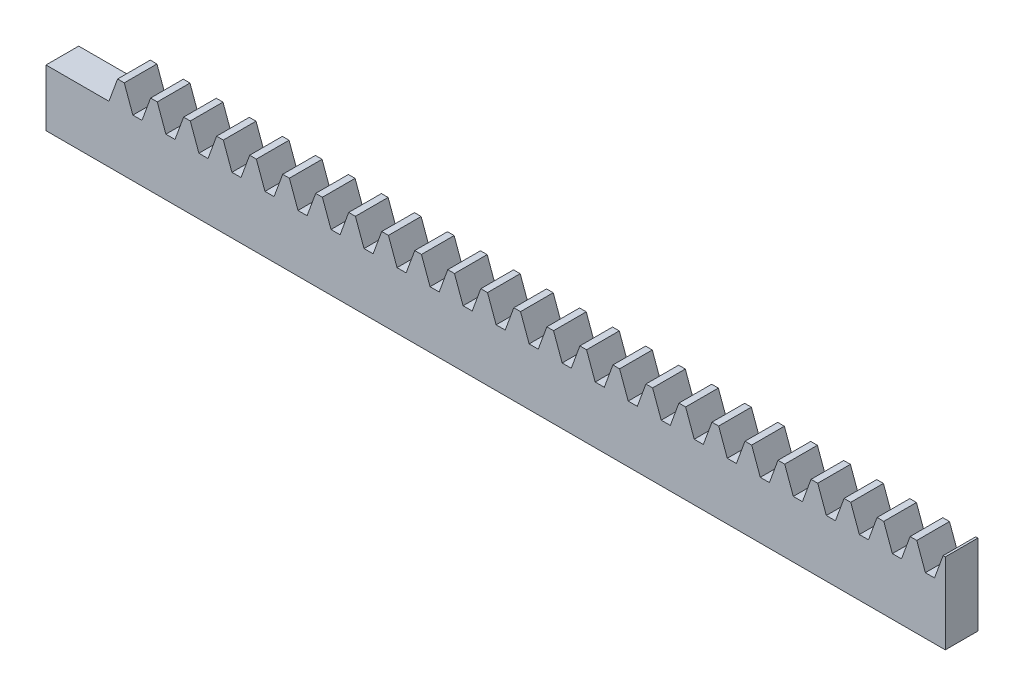
SolidWorks part; units mm, degrees
extrude "Blank" add sketch "BlankSke" against normal blind 7
sketch "BlankSke" plane through (0, 0, 0) normal (0, 0, 1) x (1, 0, 0)
  line L1 (0, 0) -> (180, 0)
  line L2 (0, 0) -> (0, 17.25)
  line L3 (0, 17.25) -> (180, 17.25)
  line L4 (180, 0) -> (180, 17.25)
  dimension "Length" = 180
  dimension "Blank_height" = 17.25
ref_plane "Plane1" through (0, 0, 0) normal (0, 0, 1) x (1, 0, 0)
ref_plane "Plane2" through (0, 0, 0) normal (0, 1, 0) x (1, 0, 0)
ref_plane "Plane3" through (0, 0, 0) normal (1, 0, 0) x (0, 0, -1)
other "Configuration Table"
sketch "HoldingSke" plane through (0, 0, 0) normal (0, 1, 0) x (1, 0, 0)
  line L0 (0, 0) -> (0.0619, 0.4401)
  line L1 (-15, 0) -> (100, 0) construction
  line L2 (0, 0) -> (-2.1039, 2.3779)
  line L3 (0, 0) -> (-11.863, 4.5341)
  line L4 (0, 0) -> (7.6947, 3.9206)
  line L5 (0, 0) -> (-23.7986, -8.8762)
  line L6 (0, 0) -> (-10.5278, -7.1032)
  line L9 (-71.009, 38.7566) -> (98.1357, 100.3202)
  line L10 (-76.2, 4.6279) -> (-61.2, 4.6279)
  line L11 (0, 0) -> (-7, 0)
  line L12 (-76.2, 101.6) -> (-76.123, 101.6)
  line L13 (24.9733, 27.94) -> (52.9518, 28.4284)
  line L14 (24.9733, 27.94) -> (24.9743, 27.94)
  line L15 (24.9733, 27.94) -> (100.4006, 29.5858)
  circle A0 centre (0, 0) radius 19.05
  circle A1 centre (0, 0) radius 7.5
  circle A2 centre (0, 0) radius 12.7
  dimension "MPH" = 15
  dimension "Diameter" = 38.1
  dimension "Num_teeth" = 27
  dimension "Pitch" = 0.4444
  dimension "Show_teeth" = 998
  dimension "Thickness" = 12.7
  dimension "Ap" = 20
  dimension "Pitch_height" = 15
  dimension "Width" = 7
  dimension "Backlash" = 0.077
  dimension "Addendum_fac" = 1
  dimension "Dedendum_fac" = 1.25
  dimension "Clearance_fac" = 0.25
  dimension "Dedendum_add" = 0.001
  dimension "Length" = 180
  dimension "Module" = 2.25
sketch "TooCutSkeIll" plane through (0, 0, 0) normal (0, 0, 1) x (1, 0, 0)
  line L0 (-2.7955, 17.1908) -> (-1.1094, 12.5583)
  line L1 (-0.5799, 12.1875) -> (0.5799, 12.1875)
  line L2 (1.1094, 12.5583) -> (2.7955, 17.1908)
  line L3 (180, 17.25) -> (0, 17.25) construction
  line L4 (0, 0) -> (0, 64.897) construction
  line L5 (-13.208, 15) -> (12.954, 15) construction
  line L6 (0, 0) -> (180, 0) construction
  line L7 (1.9981, 15) -> (1.9981, 48.7463) construction
  line L8 (-1.9981, 15) -> (-1.9981, 48.7463) construction
  line L9 (2.8801, 17.25) -> (2.8801, 17.2754)
  line L10 (-2.8801, 17.25) -> (-2.8801, 17.2754)
  line L11 (-2.8801, 17.2754) -> (2.8801, 17.2754)
  arc A0 (0.5799, 12.1875) -> (1.1094, 12.5583) centre (0.5799, 12.751) ccw
  arc A1 (-1.1094, 12.5583) -> (-0.5799, 12.1875) centre (-0.5799, 12.751) ccw
  arc A2 (2.8801, 17.25) -> (2.7955, 17.1908) centre (2.8801, 17.16) ccw
  arc A3 (-2.7955, 17.1908) -> (-2.8801, 17.25) centre (-2.8801, 17.16) ccw
  dimension "Pitch_height" = 15
  dimension "Addendum_plus" = 2.2754
  dimension "Pressure_angle" = 20
  dimension "Gap_width" = 3.9963
  dimension "Dedendum" = 2.8125
extrude "ToothCutIll" [suppressed] cut sketch "TooCutSkeIll" against normal through all
sketch "TooCutSkeSim" plane through (0, 0, 0) normal (0, 0, 1) x (1, 0, 0)
  line L0 (0.9745, 12.1875) -> (-0.9745, 12.1875)
  line L1 (2.8263, 17.2754) -> (0.9745, 12.1875)
  line L2 (0, 17.4625) -> (0, 53.467) construction
  line L3 (2.8263, 17.2754) -> (-2.8263, 17.2754)
  line L6 (-2.8263, 17.2754) -> (-0.9745, 12.1875)
  line L9 (-1.9981, 15) -> (1.9981, 15) construction
  line L10 (0, 0) -> (180, 0) construction
  line L11 (1.9981, 15) -> (1.9981, 53.467) construction
  line L12 (-1.9981, 15) -> (-1.9981, 53.467) construction
  dimension "Pitch_height" = 15
  dimension "Addendum_plus" = 2.2754
  dimension "Pressure_angle" = 20
  dimension "Gap_width" = 3.9963
  dimension "Dedendum" = 2.8125
extrude "ToothCutSim" cut sketch "TooCutSkeSim" against normal through all
pattern_linear "TeethCuts" count 26 spacing 7.0686 along (1, 0, 0) of "ToothCutIll", "ToothCutSim"
sketch "Sketch1" plane through (0, 0, 0) normal (-1, 0, 0) x (0, 0, 1)
  line L1 (-7, 0) -> (0, 0)
  line L2 (-7, 0) -> (-7, 12.1875)
  line L3 (-7, 12.1875) -> (0, 12.1875)
  line L4 (0, 0) -> (0, 12.1875)
extrude "Boss-Extrude1" add sketch "Sketch1" along normal blind 12.5
equation "' \"Module@HoldingSke\" = 6.35"
equation "' \"Num_teeth@HoldingSke\" = 12"
equation "' \"Ap@HoldingSke\" =  20"
equation "' \"Ap@HoldingSke\" = 20"
equation "' \"Width@HoldingSke\" = 0.25 * 25.4"
equation "' \"Show_teeth@HoldingSke\" = 500"
equation "' \"Backlash@HoldingSke\" = 0.009 * 25.4"
equation "' \"Addendum_fac@HoldingSke\" = 1.0"
equation "' \"Dedendum_fac@HoldingSke\" = 1.25"
equation "' \"Dedendum_add@HoldingSke\" = 0.00005 * 25.4"
equation "' \"Clearance_fac@HoldingSke\" = 0.25"
equation "' \"Pitch_height@HoldingSke\" = 1 * 25.4"
equation "' \"Length@HoldingSke\" = 4.71 * 25.4"
equation "\"Pitch@HoldingSke\" = 1 / \"Module@HoldingSke\""
equation "\"MPH@HoldingSke\" = \"Dedendum_fac@HoldingSke\" / \"Pitch@HoldingSke\" + 2 * \"Dedendum_add@HoldingSke\" + 0.002 * 25.4"
equation "\"MPH@HoldingSke\" = ((sgn( \"MPH@HoldingSke\" - \"Pitch_height@HoldingSke\")+1)*( \"MPH@HoldingSke\" - \"Pitch_height@HoldingSke\"))/2 + \"Pitch_height@HoldingSke\""
equation "\"Blank_height@BlankSke\" = \"Pitch_height@HoldingSke\" + \"Addendum_fac@HoldingSke\"  / \"Pitch@HoldingSke\" "
equation "\"Length@BlankSke\" =  \"Length@HoldingSke\""
equation "\"Face_width@Blank\" = \"Width@HoldingSke\""
equation "\"Pressure_angle@TooCutSkeIll\" = \"Ap@HoldingSke\""
equation "\"Addendum_plus@TooCutSkeIll\" =  \"Addendum_fac@HoldingSke\"  / \"Pitch@HoldingSke\" + 0.001 *25.4"
equation "\"Dedendum@TooCutSkeIll\" = \"Dedendum_fac@HoldingSke\"  / \"Pitch@HoldingSke\""
equation "\"Pitch_height@TooCutSkeIll\" =  \"MPH@HoldingSke\""
equation "\"Gap_width@TooCutSkeIll\" = 3.14159265 / 2 / \"Pitch@HoldingSke\" + 6 * \"Backlash@HoldingSke\""
equation "\"Pressure_angle@TooCutSkeSim\" = \"Ap@HoldingSke\""
equation "\"Addendum_plus@TooCutSkeSim\" =  \"Addendum_fac@HoldingSke\"  / \"Pitch@HoldingSke\" + 0.001 * 25.4"
equation "\"Dedendum@TooCutSkeSim\" = \"Dedendum_fac@HoldingSke\"  / \"Pitch@HoldingSke\""
equation "\"Pitch_height@TooCutSkeSim\" =  \"MPH@HoldingSke\""
equation "\"Gap_width@TooCutSkeSim\" = 3.14159265 / 2 / \"Pitch@HoldingSke\" + 6 * \"Backlash@HoldingSke\""
equation "\"Root_fillet@TooCutSkeIll\" = \"Clearance_fac@HoldingSke\" / \"Pitch@HoldingSke\" + \"Dedendum_add@HoldingSke\""
equation "\"Break_rad@TooCutSkeIll\" = 0.02 / \"Pitch@HoldingSke\" * 2"
equation "\"Linear_pitch@TeethCuts\" = 3.14159265 / \"Pitch@HoldingSke\""
equation "\"Num_teeth@HoldingSke\" = int( ( \"Length@HoldingSke\" + 0 ) / (3.14159265 / \"Pitch@HoldingSke\")) + 0.9999  + 1"
equation " \"Num_teeth@TeethCuts\" = int( \"Show_teeth@HoldingSke\" ) + 1"
equation " \"Num_teeth@TeethCuts\" = ((sgn( \"Num_teeth@TeethCuts\" - \"Num_teeth@HoldingSke\" )-1)*( \"Num_teeth@TeethCuts\" - \"Num_teeth@HoldingSke\" ))/-2+ \"Num_teeth@HoldingSke\""
equation " \"Num_teeth@TeethCuts\" = ((sgn( \"Num_teeth@TeethCuts\" - 2.0)+1)*( \"Num_teeth@TeethCuts\" - 2.0))/2 +2.0"
